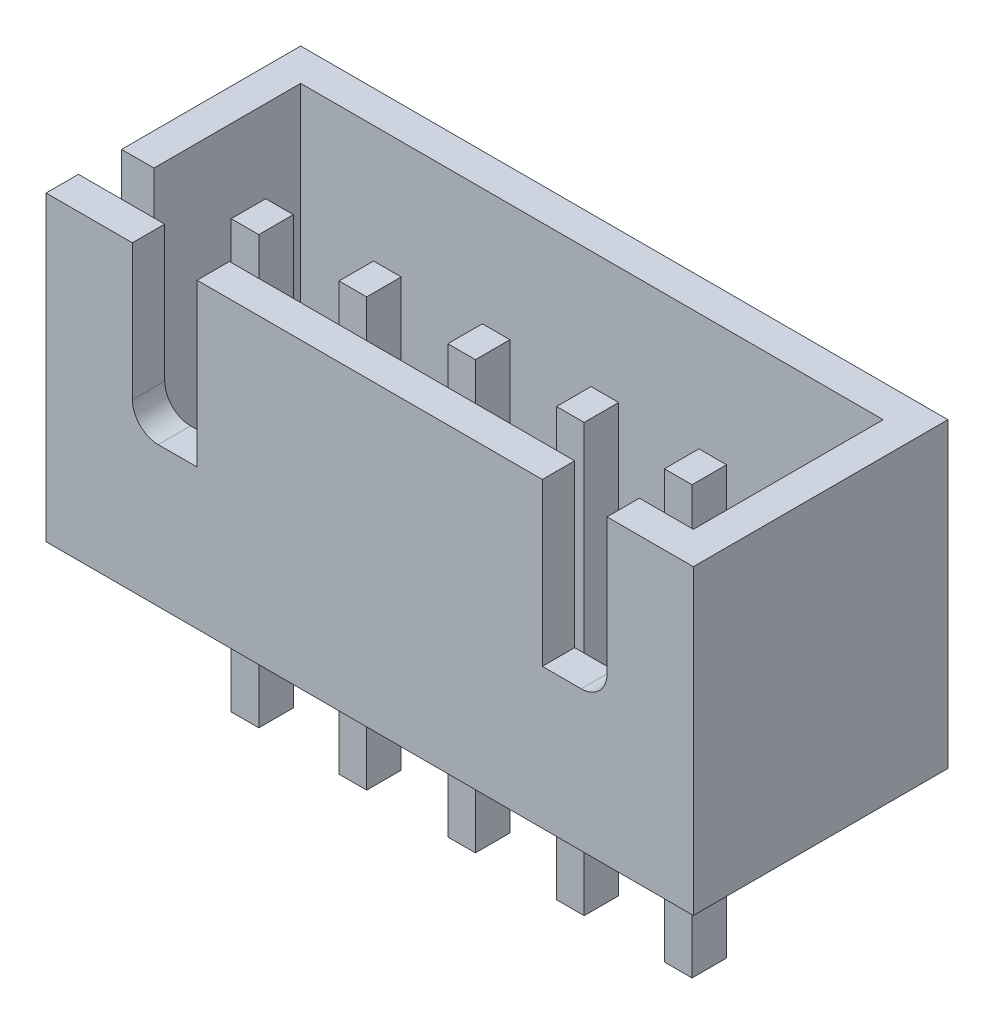
SolidWorks part; units mm, degrees
ref_plane "Alzado" through (0, 0, 0) normal (0, 0, 1) x (1, 0, 0)
ref_plane "Planta" through (0, 0, 0) normal (0, 1, 0) x (1, 0, 0)
ref_plane "Vista lateral" through (0, 0, 0) normal (1, 0, 0) x (0, 0, -1)
sketch "Croquis1" plane through (0, 0, 0) normal (0, 1, 0) x (1, 0, 0)
  line L0 (-2.48, 3.37) -> (12.52, 3.37)
  line L1 (12.52, 3.37) -> (12.52, -2.53)
  line L2 (12.52, -2.53) -> (-2.48, -2.53)
  line L3 (-2.48, -2.53) -> (-2.48, 3.37)
  line L4 (5.02, -2.53) -> (5.02, 2.1284) construction
  line L5 (-0.32, -0.4) -> (0.32, -0.4)
  line L6 (-0.32, -0.4) -> (-0.32, 0.4)
  line L7 (-0.32, 0.4) -> (0.32, 0.4)
  line L8 (0.32, -0.4) -> (0.32, 0.4)
  line L9 (-0.32, -0.4) -> (0.32, 0.4) construction
  line L10 (-0.32, 0.4) -> (0.32, -0.4) construction
  line L11 (10.36, -0.4) -> (10.36, 0.4)
  line L12 (10.36, -0.4) -> (9.72, -0.4)
  line L13 (9.72, -0.4) -> (9.72, 0.4)
  line L14 (10.36, 0.4) -> (9.72, 0.4)
  line L15 (7.22, -0.4) -> (7.22, 0.4)
  line L16 (2.18, -0.4) -> (2.82, -0.4)
  line L17 (2.18, -0.4) -> (2.18, 0.4)
  line L18 (2.18, 0.4) -> (2.82, 0.4)
  line L19 (2.82, -0.4) -> (2.82, 0.4)
  line L20 (2.18, -0.4) -> (2.82, 0.4) construction
  line L21 (2.18, 0.4) -> (2.82, -0.4) construction
  line L22 (7.86, 0.4) -> (7.22, 0.4)
  line L23 (7.86, -0.4) -> (7.86, 0.4)
  line L24 (7.86, -0.4) -> (7.22, -0.4)
  line L25 (4.7, 0.4) -> (5.34, 0.4)
  line L26 (5.34, -0.4) -> (5.34, 0.4)
  line L27 (4.7, 0.4) -> (5.34, -0.4) construction
  line L28 (4.7, -0.4) -> (5.34, 0.4) construction
  line L29 (4.7, -0.4) -> (5.34, -0.4)
  line L30 (4.7, -0.4) -> (4.7, 0.4)
  point P5 (0, 0)
  point P16 (2.5, 0)
  point P21 (5.02, 0)
  point P27 (7.54, 0)
  point P31 (5.02, 0)
  point P32 (0, 0)
  point P33 (5.34, 0.4)
  dimension "D1" = 15
  dimension "D2" = 5.9
  dimension "D3" = 3.37
  dimension "D4" = 2.48
  dimension "D5" = 0.8
  dimension "D6" = 0.64
  dimension "D7" = 2.5
extrude "Saliente-Extruir1" add sketch "Croquis1" along normal blind 1
sketch "Croquis2" plane through (0, 1, 0) normal (0, 1, 0) x (1, 0, 0)
  line L1 (-1.73, -1.78) -> (11.77, -1.78)
  line L2 (-1.73, -1.78) -> (-1.73, 2.62)
  line L3 (-1.73, 2.62) -> (11.77, 2.62)
  line L4 (-2.48, 3.37) -> (-2.48, -2.53)
  line L5 (-2.48, -2.53) -> (12.52, -2.53)
  line L6 (12.52, -2.53) -> (12.52, 3.37)
  line L7 (12.52, 3.37) -> (-2.48, 3.37)
  line L8 (-2.48, 3.37) -> (-2.48, -2.53)
  line L9 (-2.48, -2.53) -> (12.52, -2.53)
  line L10 (12.52, -2.53) -> (12.52, 3.37)
  line L11 (12.52, 3.37) -> (-2.48, 3.37)
  line L12 (11.77, -1.78) -> (11.77, 2.62)
  line L13 (-1.73, -1.78) -> (11.77, 2.62) construction
  line L14 (-1.73, 2.62) -> (11.77, -1.78) construction
  point P2 (5.02, 0.42)
  dimension "D2" = 0.75
  dimension "D3" = 0.75
  dimension "D4" = 0.75
  dimension "D5" = 0.75
  dimension "D1" = 0
extrude "Saliente-Extruir2" add sketch "Croquis2" along normal blind 6
sketch "Croquis3" plane through (-2.48, 0, 0) normal (-1, 0, 0) x (0, 0, 1)
  line L0 (1.78, 7) -> (1.78, 4.35)
  line L1 (-3.37, 7) -> (2.53, 7) construction
  line L2 (0.78, 3.75) -> (0.78, 7)
  line L3 (2.53, 7) -> (2.53, 0) construction
  line L4 (1.18, 3.75) -> (0.78, 3.75)
  line L5 (0.78, 7) -> (1.78, 7)
  arc A1 (1.18, 3.75) -> (1.78, 4.35) centre (1.18, 4.35) ccw
  dimension "D4" = 0.6
  dimension "D1" = 0.75
  dimension "D2" = 1
  dimension "D3" = 3.25
extrude "Cortar-Extruir1" cut sketch "Croquis3" against normal blind 9
sketch "Croquis4" plane through (0, 0, 2.53) normal (0, 0, 1) x (1, 0, 0)
  line L0 (-0.48, 3.85) -> (-0.48, 7)
  line L1 (-2.48, 7) -> (12.52, 7) construction
  line L3 (10.52, 3.85) -> (10.52, 7)
  line L4 (12.52, 7) -> (12.52, 0) construction
  line L5 (5.02, 0) -> (5.02, 7) construction
  line L6 (-2.48, 0) -> (12.52, 0) construction
  line L7 (-0.48, 7) -> (10.52, 7)
  line L8 (9.02, 3.25) -> (9.02, 7)
  line L9 (9.02, 3.25) -> (9.92, 3.25)
  line L10 (1.02, 3.25) -> (1.02, 7)
  line L11 (1.02, 3.25) -> (0.12, 3.25)
  arc A0 (9.92, 3.25) -> (10.52, 3.85) centre (9.92, 3.85) ccw
  arc A1 (0.12, 3.25) -> (-0.48, 3.85) centre (0.12, 3.85) cw
  point P18 (5.02, 3.25)
  point P21 (0, 0)
  point P22 (0, 0)
  line M11 (12.52, 7) -> (-2.48, 7)
  dimension "D2" = 0.6
  dimension "D1" = 2
  dimension "D3" = 3.75
  dimension "D4" = 1.5
extrude "Cortar-Extruir2" cut sketch "Croquis4" against normal blind 2 contours A1 L11 L10 L0 M11 | L9 A0 L3 L8 M11
sketch "Croquis5" plane through (0, 0, 0) normal (0, 1, 0) x (1, 0, 0)
  line L0 (10.36, -0.4) -> (10.36, 0.4) construction
  line L1 (9.72, -0.4) -> (10.36, -0.4) construction
  line L2 (9.72, 0.4) -> (9.72, -0.4) construction
  line L3 (10.36, 0.4) -> (9.72, 0.4) construction
  line L4 (0.32, 0.4) -> (-0.32, 0.4) construction
  line L5 (0.32, -0.4) -> (0.32, 0.4) construction
  line L6 (-0.32, -0.4) -> (0.32, -0.4) construction
  line L7 (-0.32, 0.4) -> (-0.32, -0.4) construction
  line L8 (10.36, -0.4) -> (10.36, 0.4)
  line L9 (9.72, -0.4) -> (10.36, -0.4)
  line L10 (9.72, 0.4) -> (9.72, -0.4)
  line L11 (10.36, 0.4) -> (9.72, 0.4)
  line L12 (0.32, 0.4) -> (-0.32, 0.4)
  line L13 (0.32, -0.4) -> (0.32, 0.4)
  line L14 (-0.32, -0.4) -> (0.32, -0.4)
  line L15 (-0.32, 0.4) -> (-0.32, -0.4)
  line L16 (2.82, -0.4) -> (2.82, 0.4) construction
  line L17 (2.18, -0.4) -> (2.82, -0.4) construction
  line L18 (2.18, 0.4) -> (2.18, -0.4) construction
  line L19 (2.82, 0.4) -> (2.18, 0.4) construction
  line L20 (2.82, -0.4) -> (2.82, 0.4)
  line L21 (2.18, -0.4) -> (2.82, -0.4)
  line L22 (2.18, 0.4) -> (2.18, -0.4)
  line L23 (2.82, 0.4) -> (2.18, 0.4)
  line L24 (7.22, -0.4) -> (7.86, -0.4) construction
  line L25 (7.22, 0.4) -> (7.22, -0.4) construction
  line L26 (7.86, 0.4) -> (7.22, 0.4) construction
  line L27 (7.86, -0.4) -> (7.86, 0.4) construction
  line L28 (7.22, -0.4) -> (7.86, -0.4)
  line L29 (7.22, 0.4) -> (7.22, -0.4)
  line L30 (7.86, 0.4) -> (7.22, 0.4)
  line L31 (7.86, -0.4) -> (7.86, 0.4)
  line L32 (5.34, -0.4) -> (5.34, 0.4) construction
  line L33 (4.7, -0.4) -> (5.34, -0.4) construction
  line L34 (4.7, 0.4) -> (4.7, -0.4) construction
  line L35 (5.34, 0.4) -> (4.7, 0.4) construction
  line L36 (5.34, -0.4) -> (5.34, 0.4)
  line L37 (4.7, -0.4) -> (5.34, -0.4)
  line L38 (4.7, 0.4) -> (4.7, -0.4)
  line L39 (5.34, 0.4) -> (4.7, 0.4)
extrude "Saliente-Extruir3" add sketch "Croquis5" along normal blind 6.5 and the other way blind 3.4
